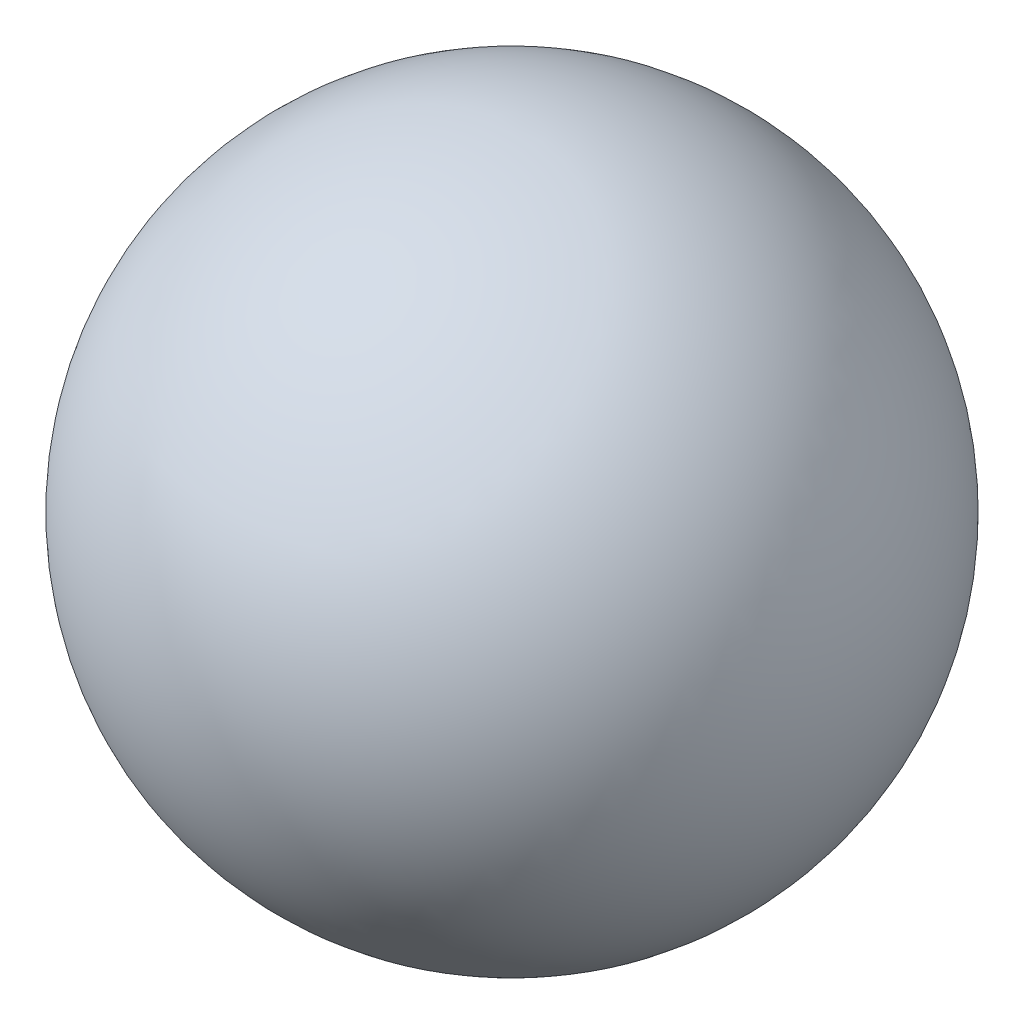
SolidWorks part; units mm, degrees
ref_plane "Front Plane" through (0, 0, 0) normal (0, 0, 1) x (1, 0, 0)
ref_plane "Top Plane" through (0, 0, 0) normal (0, 1, 0) x (1, 0, 0)
ref_plane "Right Plane" through (0, 0, 0) normal (1, 0, 0) x (0, 0, -1)
sketch "Sketch1" plane through (0, 0, 0) normal (0, 0, 1) x (1, 0, 0)
  line L0 (0, -1.75) -> (0, 1.75)
  arc A0 (0, 1.75) -> (0, -1.75) centre (0, 0) ccw
  dimension "D1" = 3.5
revolve "Revolve1" add sketch "Sketch1" angle 360 about L0
